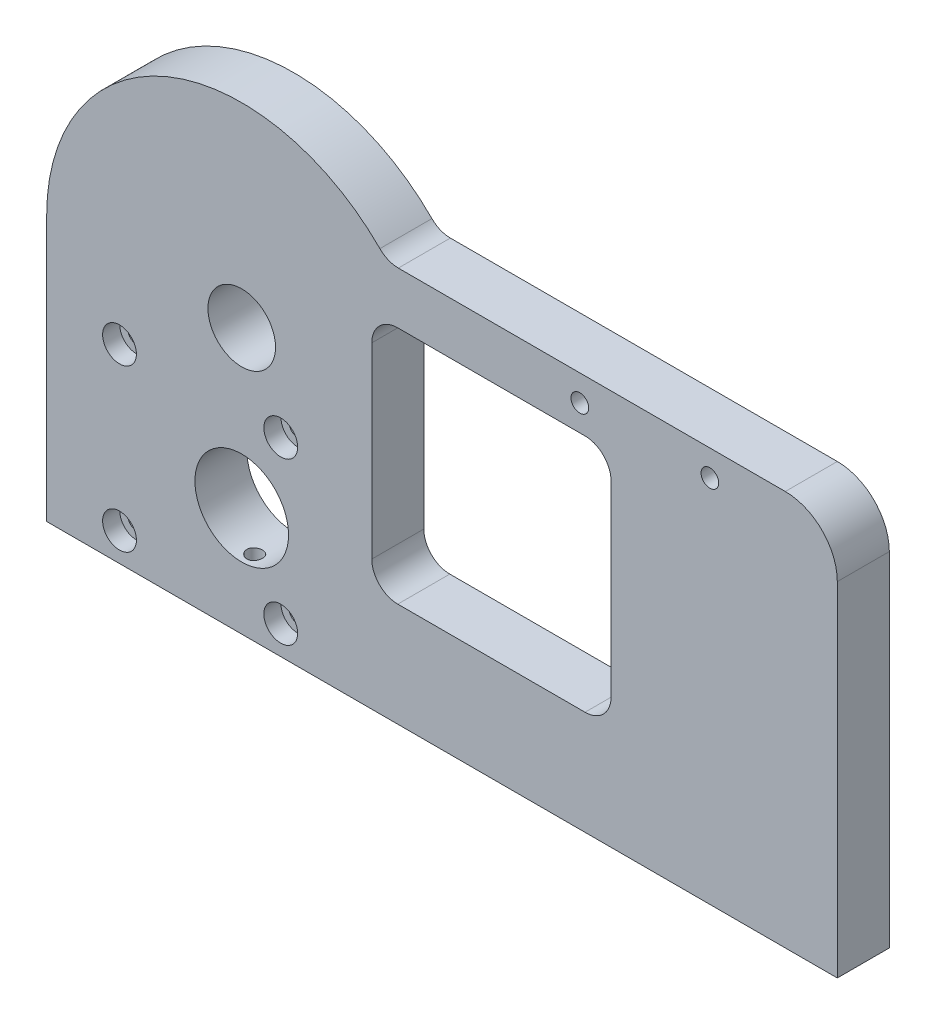
SolidWorks part; units mm, degrees
ref_plane "Front Plane" through (0, 0, 0) normal (0, 0, 1) x (1, 0, 0)
ref_plane "Top Plane" through (0, 0, 0) normal (0, 1, 0) x (1, 0, 0)
ref_plane "Right Plane" through (0, 0, 0) normal (1, 0, 0) x (0, 0, -1)
sketch "Sketch1" plane through (0, 0, 0) normal (0, 0, 1) x (1, 0, 0)
  line L1 (0, 0) -> (152, 0)
  line L2 (0, 0) -> (0, 51)
  line L3 (65.4508, 76) -> (152, 76)
  line L4 (152, 0) -> (152, 76)
  arc A0 (65.4508, 76) -> (0, 51) centre (37.5, 51) ccw
extrude "Boss-Extrude1" add sketch "Sketch1" along normal blind 10
fillet "Fillet1" radius 5 1 edges at (65.4508, 76, 5)
fillet "Fillet2" radius 10 1 edges at (152, 76, 5)
sketch "Sketch2" plane through (0, 0, 10) normal (0, 0, 1) x (1, 0, 0)
  circle A0 centre (37.5, 21) radius 9
extrude "Cut-Extrude1" cut sketch "Sketch2" against normal through all
sketch "Sketch3" plane through (0, 0, 10) normal (0, 0, 1) x (1, 0, 0)
  circle A0 centre (37.5, 51) radius 6.5
extrude "Cut-Extrude2" cut sketch "Sketch3" against normal through all
sketch "Sketch4" plane through (0, 0, 10) normal (0, 0, 1) x (1, 0, 0)
  line L1 (62.5, 20) -> (108.5, 20)
  line L2 (62.5, 20) -> (62.5, 66)
  line L3 (62.5, 66) -> (108.5, 66)
  line L4 (108.5, 20) -> (108.5, 66)
  line L5 (62.5, 20) -> (108.5, 66) construction
  line L6 (62.5, 66) -> (108.5, 20) construction
  point P4 (95.4918, 45.3854)
extrude "Cut-Extrude3" cut sketch "Sketch4" against normal through all
sketch "Sketch5" plane through (0, 0, 0) normal (0, -1, 0) x (1, 0, 0)
  circle A0 centre (37.5, 7.5) radius 1.5
  point P2 (0, 0)
extrude "Cut-Extrude4" cut sketch "Sketch5" against normal up to next
fillet "Fillet3" radius 5 4 edges at (62.5, 20, 5) (108.5, 20, 5) (62.5, 66, 5) (108.5, 66, 5)
sketch "Sketch8" plane through (0, 0, 10) normal (0, 0, 1) x (1, 0, 0)
  point P0 (14, 36.5)
  point P2 (45, 36.5)
  point P4 (45, 5.5)
  point P6 (14, 5.5)
sketch "Sketch6" plane through (0, 0, 0) normal (0, -1, 0) x (-1, 0, 0)
  point P0 (-16, -5)
  point P2 (-56, -5)
  point P4 (-96, -5)
  point P6 (-136, -5)
hole_wizard "M3x0.5 Tapped Hole1" positions "Sketch6" profile "Sketch7" tap size "M3x0.5" standard "JIS"
sketch "Sketch7" plane through (16, 0, 5) normal (1, 0, 0) x (0, 0, -1)
  line L0 (0, 0) -> (0, 9.7811)
  line L1 (0, 9.7811) -> (1.3, 9)
  line L2 (1.3, 9) -> (1.3, 0)
  line L5 (1.3, 0) -> (0, 0)
  line L10 (0, 9.7811) -> (-1.3, 9) construction
  line L11 (0, -6.35) -> (0, 107.95) construction
  dimension "Tap Drill Dia." = 2.6
  dimension "Tap Drill Depth" = 9
  dimension "Drill Angle" = 118
cosmetic thread "Hole Thread1" parameters "D1"=6, "D2"=3
cosmetic thread "Hole Thread2" parameters "D1"=6, "D2"=3
cosmetic thread "Hole Thread3" parameters "D1"=6, "D2"=3
cosmetic thread "Hole Thread4" parameters "D1"=6, "D2"=3
hole_wizard "CBORE for M3 Pan Head Screw1" positions "Sketch8" profile "Sketch9" counterbore size "M3" standard "JIS" end condition through all
sketch "Sketch9" plane through (14, 36.5, 10) normal (1, 0, 0) x (0, -1, 0)
  line L0 (0, 0) -> (0, 10)
  line L1 (0, 10) -> (1.7, 10)
  line L3 (1.7, 10) -> (1.7, 3.3)
  line L4 (1.7, 3.3) -> (3.25, 3.3)
  line L5 (3.25, 3.3) -> (3.25, 0)
  line L7 (3.25, 0) -> (0, 0)
  line L11 (0, -6.35) -> (0, 107.95) construction
  dimension "Thru Hole Dia." = 3.4
  dimension "Thru Hole Depth" = 10
  dimension "C'Bore Dia." = 6.5
  dimension "C'Bore Depth" = 3.3
sketch "Sketch10" plane through (0, 0, 0) normal (0, 0, -1) x (-1, 0, 0)
  point P0 (-127.5, 71)
  point P2 (-102.5, 71)
hole_wizard "CBORE for M3 Pan Head Screw2" positions "Sketch10" profile "Sketch11" counterbore size "M3" standard "JIS" end condition through all
sketch "Sketch11" plane through (127.5, 71, 0) normal (1, 0, 0) x (0, 1, 0)
  line L0 (0, 0) -> (0, 10)
  line L1 (0, 10) -> (1.7, 10)
  line L3 (1.7, 10) -> (1.7, 3.3)
  line L4 (1.7, 3.3) -> (3.25, 3.3)
  line L5 (3.25, 3.3) -> (3.25, 0)
  line L7 (3.25, 0) -> (0, 0)
  line L11 (0, -6.35) -> (0, 107.95) construction
  dimension "Thru Hole Dia." = 3.4
  dimension "Thru Hole Depth" = 10
  dimension "C'Bore Dia." = 6.5
  dimension "C'Bore Depth" = 3.3
